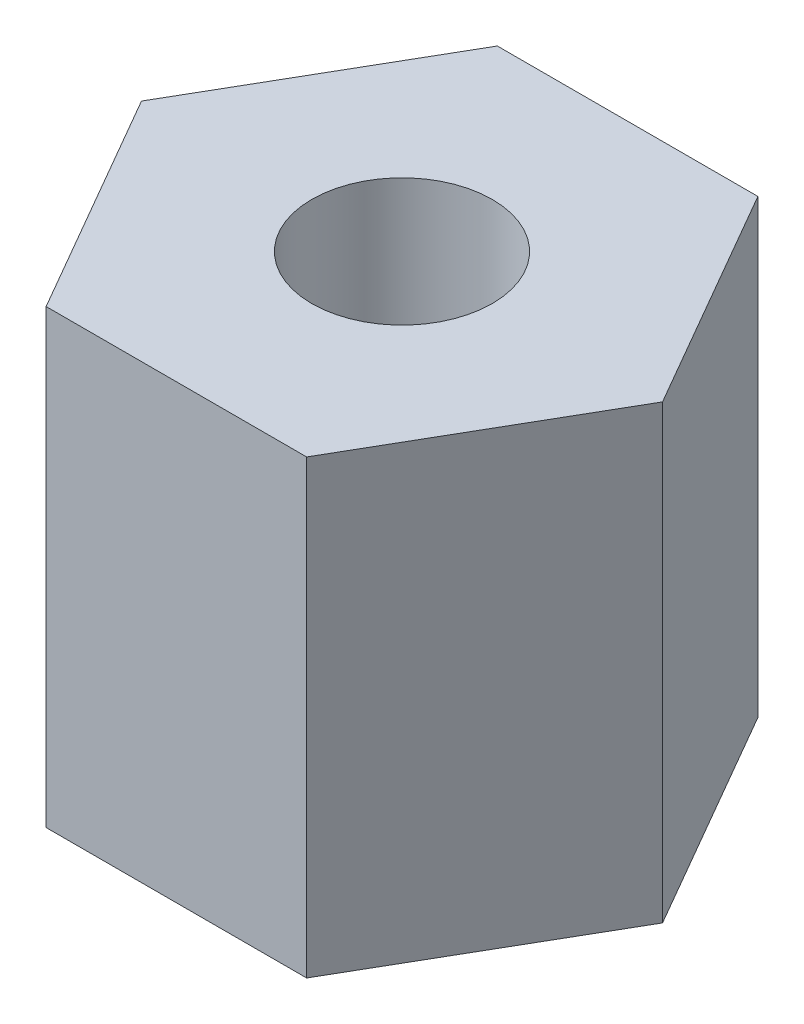
SolidWorks part; units mm, degrees
ref_plane "Front Plane" through (0, 0, 0) normal (0, 0, 1) x (1, 0, 0)
ref_plane "Top Plane" through (0, 0, 0) normal (0, 1, 0) x (1, 0, 0)
ref_plane "Right Plane" through (0, 0, 0) normal (1, 0, 0) x (0, 0, -1)
sketch "Sketch1" plane through (0, 0, 0) normal (0, 1, 0) x (1, 0, 0)
  line L1 (-14.4338, 25) -> (-28.8675, 0)
  line L2 (-28.8675, 0) -> (-14.4338, -25)
  line L3 (-14.4338, -25) -> (14.4338, -25)
  line L4 (14.4338, -25) -> (28.8675, 0)
  line L5 (28.8675, 0) -> (14.4338, 25)
  line L6 (14.4338, 25) -> (-14.4338, 25)
  circle A0 centre (0, 0) radius 25 construction
  dimension "D1" = 50
extrude "Boss-Extrude1" add sketch "Sketch1" along normal blind 50
sketch "Sketch3" plane through (0, 50, 0) normal (0, 1, 0) x (1, 0, 0)
  circle A0 centre (0, 0) radius 10
  dimension "D1" = 20
extrude "Cut-Extrude1" cut sketch "Sketch3" against normal through all both and the other way through all
equation "\"width\"=50"
equation "\"D1@Sketch1\"=\"width\""
equation "\"height\"=50"
equation "\"D1@Boss-Extrude1\"=\"height\""
equation "\"hole_dia\"=20"
equation "\"D1@Sketch3\"=\"hole_dia\""
